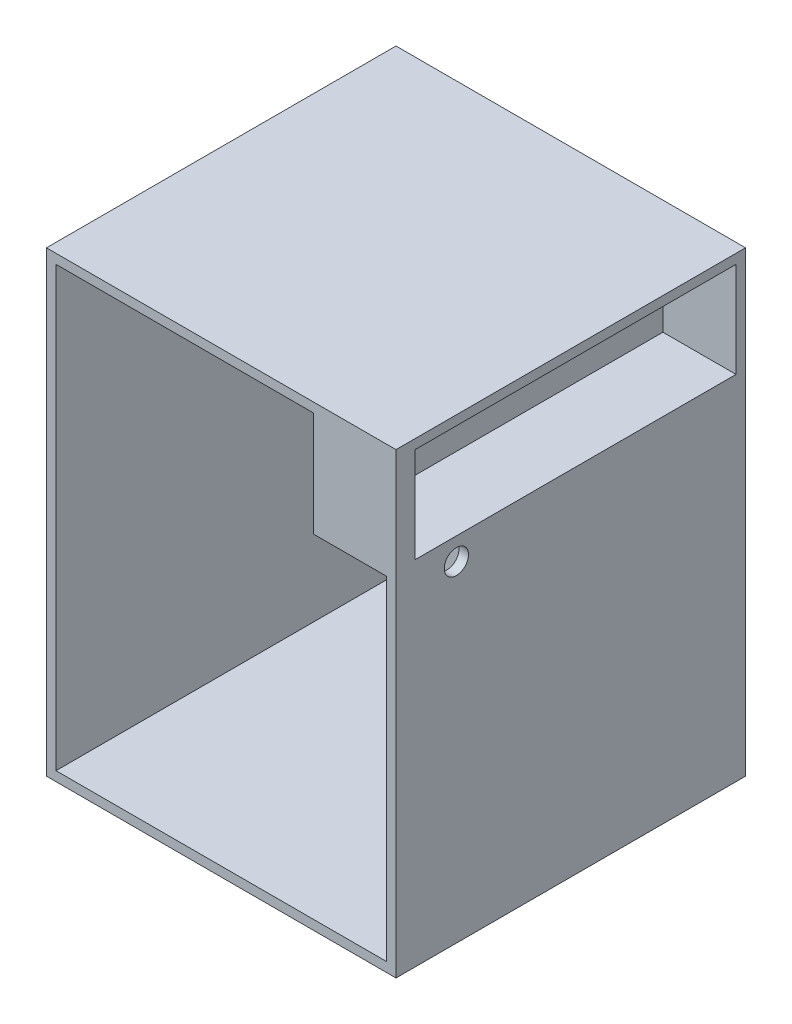
SolidWorks part; units mm, degrees
material "Balsa"
ref_plane "Alzado" through (0, 0, 0) normal (0, 0, 1) x (1, 0, 0)
ref_plane "Planta" through (0, 0, 0) normal (0, 1, 0) x (1, 0, 0)
ref_plane "Vista lateral" through (0, 0, 0) normal (1, 0, 0) x (0, 0, -1)
sketch "Croquis1" plane through (0, 0, 0) normal (0, 1, 0) x (1, 0, 0)
  line L1 (275, -275) -> (-275, -275)
  line L2 (275, -275) -> (275, 275)
  line L3 (275, 275) -> (-275, 275)
  line L4 (-275, -275) -> (-275, 275)
  line L5 (275, -275) -> (-275, 275) construction
  line L6 (275, 275) -> (-275, -275) construction
  point P0 (0, 0)
  dimension "D1" = 550
  dimension "D2" = 550
extrude "Saliente-Extruir1" add sketch "Croquis1" along normal blind 720
shell "Vaciado1" thickness 15
sketch "Croquis2" plane through (0, 0, 275) normal (0, 0, 1) x (1, 0, 0)
  line L11 (160, 705) -> (160, 555)
  line L17 (-260, 705) -> (260, 705) construction
  line L18 (160, 555) -> (260, 555)
  line L19 (260, 705) -> (260, 15) construction
  line L20 (145, 705) -> (145, 540)
  line L21 (145, 540) -> (260, 540)
  line L22 (145, 705) -> (160, 705)
  line L23 (260, 555) -> (260, 540)
  dimension "D1" = 100
  dimension "D2" = 150
  dimension "D3" = 15
extrude "Saliente-Extruir2" add sketch "Croquis2" against normal up to vertex (535 mm away)
sketch "Croquis3" plane through (275, 0, 0) normal (1, 0, 0) x (0, 0, -1)
  line L0 (-275, 705) -> (260, 705) construction
  line L1 (-245, 705) -> (260, 705)
  line L2 (-245, 705) -> (-245, 555)
  line L3 (-245, 555) -> (260, 555)
  line L4 (260, 705) -> (260, 555)
  line L5 (260, 555) -> (-275, 555) construction
  line L6 (260, 705) -> (260, 555) construction
  line L8 (-275, 720) -> (-275, 0) construction
  dimension "D1" = 30
extrude "Cortar-Extruir1" cut sketch "Croquis3" against normal up to surface (115 mm away) up to face at (160, 630, 7.5)
sketch "Croquis4" plane through (160, 0, 0) normal (1, 0, 0) x (0, 0, -1)
  line L1 (-275, 705) -> (-260, 705)
  line L2 (-275, 705) -> (-275, 555)
  line L3 (-275, 555) -> (-260, 555)
  line L4 (-260, 705) -> (-260, 555)
  dimension "D1" = 15
extrude "Saliente-Extruir3" add sketch "Croquis4" along normal up to vertex (100 mm away)
sketch "Croquis5" plane through (-275, 0, 0) normal (-1, 0, 0) x (0, 0, 1)
  line L1 (-275, 720) -> (-275, 0) construction
  line L2 (-275, 720) -> (275, 720) construction
  circle A0 centre (-180, 520) radius 19.05
  dimension "D2" = 38.1
  dimension "D1" = 95
  dimension "D3" = 200
extrude "Cortar-Extruir2" cut sketch "Croquis5" against normal blind 30
sketch "Croquis6" plane through (275, 0, 0) normal (1, 0, 0) x (0, 0, -1)
  line L0 (-275, 720) -> (-275, 0) construction
  line L1 (-275, 720) -> (275, 720) construction
  circle A0 centre (-180, 520) radius 19.05
  dimension "D3" = 38.1
  dimension "D1" = 95
  dimension "D2" = 200
extrude "Cortar-Extruir3" cut sketch "Croquis6" against normal blind 30
